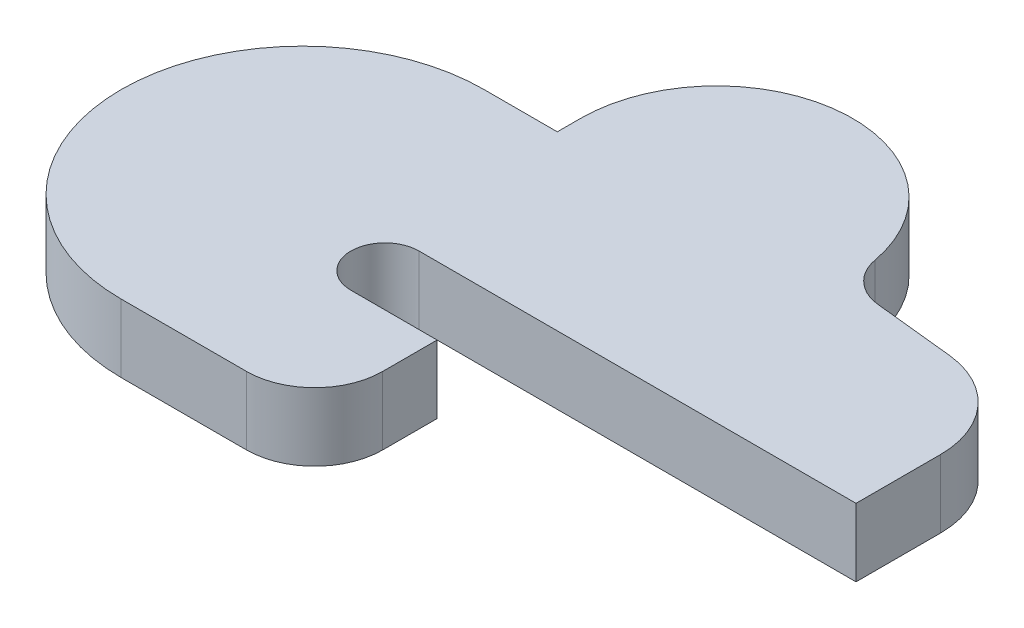
SolidWorks part; units mm, degrees
ref_plane "Front Plane" through (0, 0, 0) normal (0, 0, 1) x (1, 0, 0)
ref_plane "Top Plane" through (0, 0, 0) normal (0, 1, 0) x (1, 0, 0)
ref_plane "Right Plane" through (0, 0, 0) normal (1, 0, 0) x (0, 0, -1)
sketch "Sketch1" plane through (0, 0, 0) normal (0, 1, 0) x (1, 0, 0)
  line L0 (0, 0) -> (-3.8, 0)
  line L1 (-3.8, 3) -> (15.47, 3)
  line L2 (15.47, 3) -> (15.47, 6.7294)
  line L7 (-5.3, 10.6) -> (-8.53, 10.6)
  line L9 (0, -2.4) -> (0, 0)
  line L10 (-8.53, -5.4) -> (-3, -5.4)
  line L11 (8.3598, 11.0783) -> (11.8881, 10.7074)
  line L12 (-5.3, 10.6) -> (-5.3, 11.6246)
  arc A0 (-3.8, 0) -> (-3.8, 3) centre (-3.8, 1.5) cw
  arc A5 (-8.53, 10.6) -> (-8.53, -5.4) centre (-8.53, 2.6) ccw
  arc A10 (-3, -5.4) -> (0, -2.4) centre (-3, -2.4) ccw
  arc A11 (-5.3, 11.6246) -> (6.6016, 12.7067) centre (0.7, 11.6246) cw
  arc A12 (6.6016, 12.7067) -> (8.3598, 11.0783) centre (8.5688, 13.0673) ccw
  arc A13 (15.47, 6.7294) -> (11.8881, 10.7074) centre (11.47, 6.7294) ccw
  point P10 (0.1568, 17.6)
  point P15 (6.6885, 11.2539)
  point P17 (7.2098, 11.6)
  point P19 (-16.53, 2.6)
  point P44 (-5.3, 1.5)
  dimension "10.9" = 8
  dimension "D4" = 1.5
  dimension "D5" = 23
  dimension "D6" = 6
  dimension "D7" = 2
  dimension "D10" = 32
  dimension "D11" = 3
  dimension "D2" = 6
  dimension "D8" = 4
  dimension "13.48" = 19.27
  dimension "80" = 90
  dimension "D9" = 3.8
  dimension "D37" = 8.6
  dimension "D12" = 1.1
extrude "Boss-Extrude2" add sketch "Sketch1" along normal blind 3
